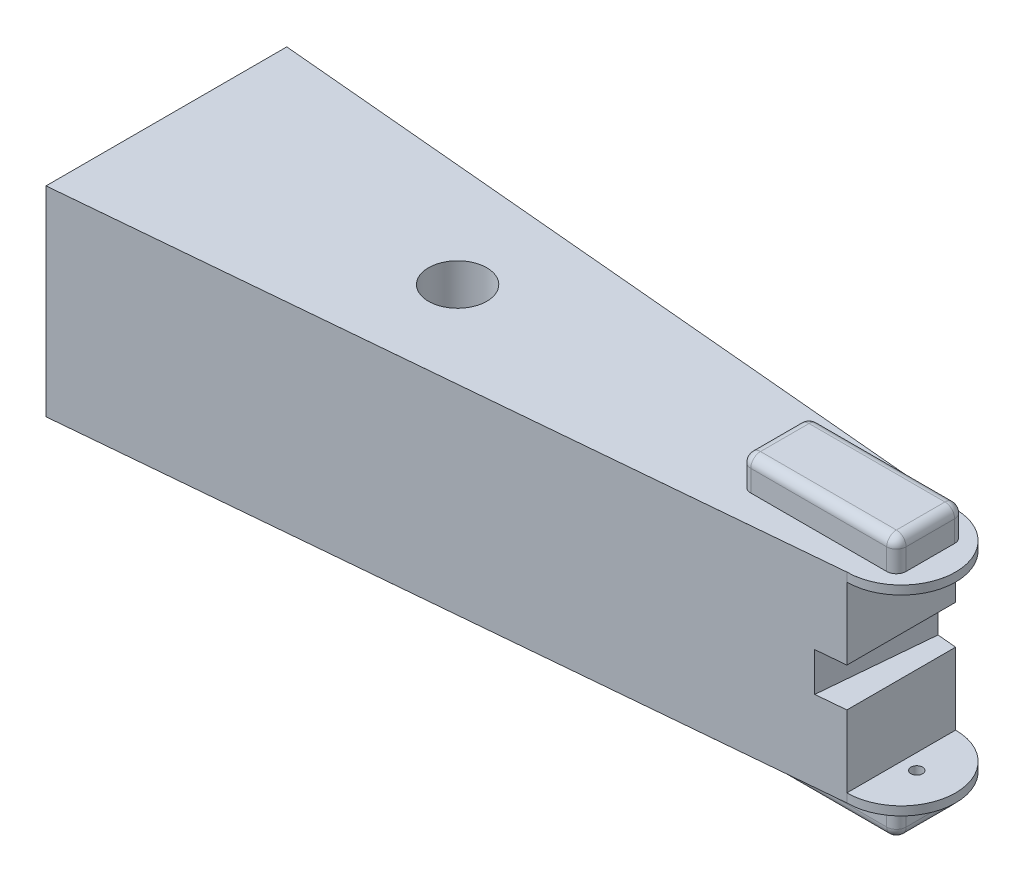
SolidWorks part; units mm, degrees
material "1060 Alloy"
ref_plane "Front Plane" through (0, 0, 0) normal (0, 0, 1) x (1, 0, 0)
ref_plane "Top Plane" through (0, 0, 0) normal (0, 1, 0) x (1, 0, 0)
ref_plane "Right Plane" through (0, 0, 0) normal (1, 0, 0) x (0, 0, -1)
sketch "Sketch1" plane through (0, 0, 0) normal (0, 1, 0) x (1, 0, 0)
  line L0 (0, -62) -> (0, 62)
  line L1 (0, 62) -> (378.4759, 28)
  line L2 (0, -62) -> (378.4759, -28)
  arc A1 (378.4759, -28) -> (378.4759, 28) centre (378.4759, 0) ccw
  point P6 (0, 0)
  dimension "D4" = 380
  dimension "D1" = 56
  dimension "D2" = 124
  dimension "D3" = 380
extrude "Boss-Extrude1" add sketch "Sketch1" along normal blind 103
fillet "Fillet1" radius 0.001 12 edges at (378.4759, 51.5, 28) (406.4759, 103, 0) (378.4759, 51.5, -28) (406.4759, 0, 0) (0, 51.5, -62) (0, 103, 0) (0, 51.5, 62) (0, 0, 0) (189.2379, 0, 45) (189.2379, 0, -45) (189.2379, 103, 45) (189.2379, 103, -45)
sketch "Sketch3" plane through (0, 0, 0) normal (0, -1, 0) x (-1, 0, 0)
  line L1 (-393.4759, -17.5) -> (-313.4759, -17.5)
  line L2 (-393.4759, -17.5) -> (-393.4759, 17.5)
  line L3 (-393.4759, 17.5) -> (-313.4759, 17.5)
  line L4 (-313.4759, -17.5) -> (-313.4759, 17.5)
  line L5 (-393.4759, -17.5) -> (-313.4759, 17.5) construction
  line L6 (-393.4759, 17.5) -> (-313.4759, -17.5) construction
  point P0 (-378.4759, 0)
  point P1 (-353.4759, 0)
  dimension "D1" = 80
  dimension "D2" = 35
  dimension "D3" = 15
extrude "Boss-Extrude2" add sketch "Sketch3" along normal blind 16
fillet "Fillet2" radius 5 8 edges at (393.4759, -8, -17.5) (313.4759, -8, -17.5) (313.4759, -8, 17.5) (393.4759, -8, 17.5) (393.4759, -16, 0) (353.4759, -16, -17.5) (313.4759, -16, 0) (353.4759, -16, 17.5)
sketch "Sketch4" plane through (0, 0, 0) normal (0, -1, 0) x (1, 0, 0)
  line L0 (0.001, 61.9989) -> (0.001, -61.9989) construction
  circle A0 centre (150.001, 0) radius 15
  dimension "D1" = 30
  dimension "D2" = 150
extrude "Cut-Extrude1" cut sketch "Sketch4" against normal through all
ref_plane "Plane1" through (0, 51.5, 0) normal (0, -1, 0) x (-1, 0, 0)
sketch "Sketch15" plane through (0, 51.5, 0) normal (0, -1, 0) x (-1, 0, 0)
  line L0 (-378.4759, 29) -> (-378.4759, -29) construction
  line L1 (-378.4759, 29) -> (-378.4759, -29)
  arc A0 (-378.4759, 29) -> (-378.4759, -29) centre (-378.4759, 0) ccw
  dimension "D1" = 29
extrude "Cut-Extrude10" cut sketch "Sketch15" against normal mid plane 94
sketch "Sketch17" plane through (5.5251, 0, -61.5037) normal (0.0895, 0, -0.996) x (-0.996, 0, -0.0895)
  line L0 (-374.4526, 102.999) -> (-374.4526, 0.001) construction
  line L1 (-384.4526, 41.5) -> (-364.4526, 41.5)
  line L2 (-384.4526, 41.5) -> (-384.4526, 61.5)
  line L3 (-384.4526, 61.5) -> (-364.4526, 61.5)
  line L4 (-364.4526, 41.5) -> (-364.4526, 61.5)
  line L5 (-384.4526, 41.5) -> (-364.4526, 61.5) construction
  line L6 (-384.4526, 61.5) -> (-364.4526, 41.5) construction
  point P0 (-374.4526, 51.5)
  dimension "D1" = 20
  dimension "D2" = 20
extrude "Cut-Extrude13" cut sketch "Sketch17" against normal blind 94
mirror "Mirror1" about plane through (0, 51.5, 0) normal (0, -1, 0) of "Fillet2", "Boss-Extrude2"
sketch "Sketch19" plane through (0, 4.5, 0) normal (0, 1, 0) x (1, 0, 0)
  line L0 (378.4759, -28) -> (378.4759, 28) construction
  circle A0 centre (386.4759, 0) radius 3
  arc A2 (378.4759, -28) -> (378.4759, 28) centre (378.4759, 0) ccw construction
  dimension "D1" = 6
  dimension "D2" = 8
  dimension "D3" = 0
extrude "Cut-Extrude14" cut sketch "Sketch19" against normal blind 10
sketch "Sketch20" plane through (0, 98.5, 0) normal (0, -1, 0) x (1, 0, 0)
  line L0 (378.4759, 28) -> (378.4759, -28) construction
  circle A0 centre (386.4759, 0) radius 3
  arc A1 (378.4759, -28) -> (378.4759, 28) centre (378.4759, 0) ccw construction
  dimension "D1" = 6
  dimension "D2" = 8
  dimension "D3" = 0
extrude "Cut-Extrude15" cut sketch "Sketch20" against normal blind 10
